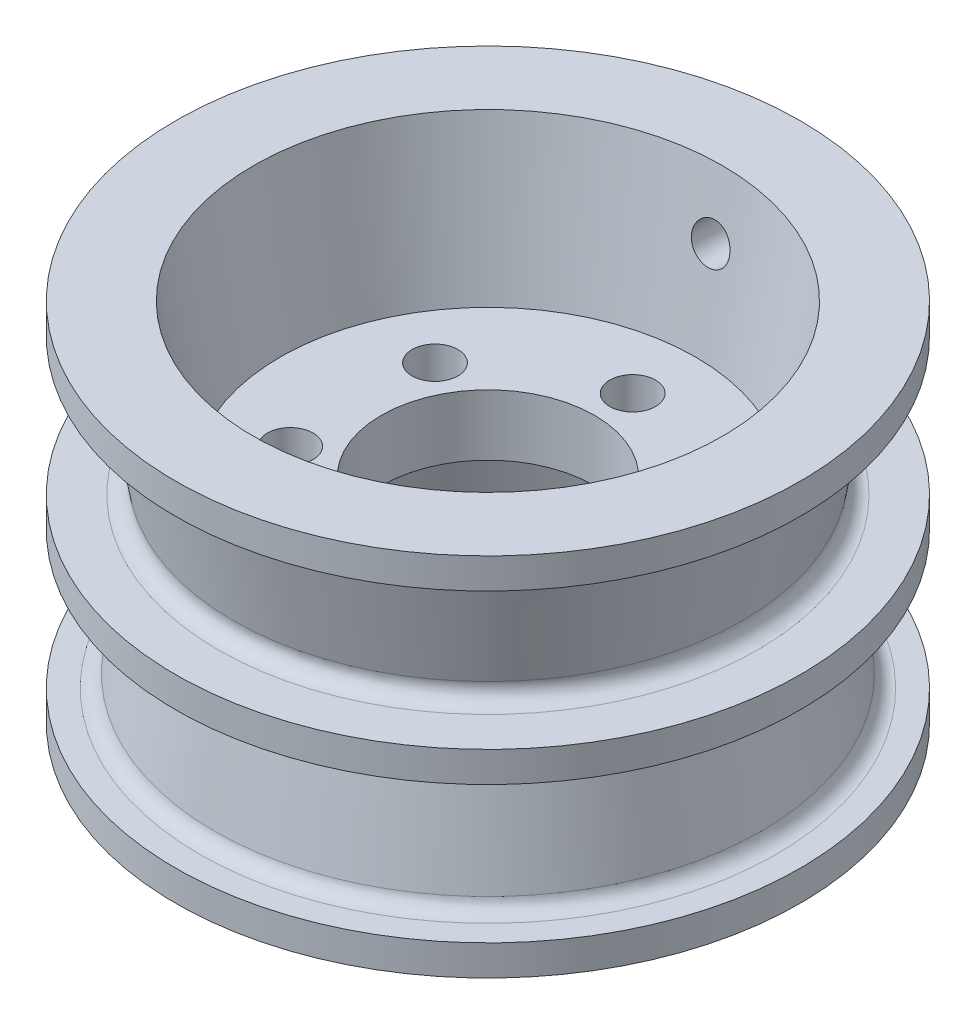
SolidWorks part; units mm, degrees
material "PA Type 6 尼龙"
ref_plane "前视基准面" through (0, 0, 0) normal (0, 0, 1) x (1, 0, 0)
ref_plane "上视基准面" through (0, 0, 0) normal (0, 1, 0) x (1, 0, 0)
ref_plane "右视基准面" through (0, 0, 0) normal (1, 0, 0) x (0, 0, -1)
sketch "草图2" plane through (0, 0, 0) normal (1, 0, 0) x (0, 0, -1)
  line L0 (20.5, 12) -> (20.5, 10)
  line L1 (20.5, 10) -> (18.0869, 10)
  line L2 (18.0869, 10) -> (16.5, 1)
  line L3 (16.5, 1) -> (20.5, 1)
  line L4 (20.5, 1) -> (20.5, -1)
  line L5 (20.5, -1) -> (16.5, -1)
  line L6 (16.5, -1) -> (18.0869, -10)
  line L7 (18.0869, -10) -> (20.5, -10)
  line L8 (20.5, -10) -> (20.5, -12)
  line L9 (20.5, -12) -> (15.3933, -12)
  line L10 (15.3933, -12) -> (13.63, -2)
  line L11 (13.63, -2) -> (0, -2)
  line L12 (0, -2) -> (0, 2)
  line L13 (0, 2) -> (13.63, 2)
  line L14 (13.63, 2) -> (15.3933, 12)
  line L15 (15.3933, 12) -> (20.5, 12)
  line L16 (0, 0) -> (20.5, 0) construction
  dimension "D1" = 4
  dimension "D2" = 2
  dimension "D3" = 24
  dimension "D4" = 10
  dimension "D5" = 16.5
  dimension "D6" = 3
  dimension "D7" = 20.5
revolve "旋转1" add sketch "草图2" angle 360 about L12
fillet "圆角1" radius 1 4 edges at (0, -10, -18.0869) (0, -1, -16.5) (0, 1, -16.5) (0, 10, -18.0869)
sketch "草图3" plane through (0, 2, 0) normal (0, 1, 0) x (1, 0, 0)
  circle A0 centre (0, 0) radius 7
  dimension "D1" = 14
extrude "切除-拉伸1" cut sketch "草图3" against normal blind 10
sketch "草图5" plane through (0, 0, 0) normal (0, 0, 1) x (1, 0, 0)
  line L0 (0, 7.9236) -> (0, 0) construction
  line L1 (-17.9412, 9.1736) -> (17.9412, 9.1736) construction
  circle A0 centre (0, 7.9236) radius 1.25
  dimension "D1" = 2.5
extrude "切除-拉伸2" cut sketch "草图5" against normal blind 24
mirror "镜向1" about plane through (0, 0, 0) normal (0, 1, 0) of "切除-拉伸2"
sketch "草图6" plane through (0, -2, 0) normal (0, -1, 0) x (1, 0, 0)
  circle A0 centre (0, 0) radius 9.5 construction
  circle A1 centre (0, 9.5) radius 1.505
  dimension "D1" = 19
  dimension "D2" = 3.01
extrude "切除-拉伸3" cut sketch "草图6" against normal blind 10
pattern_circular "阵列(圆周)1" count 6 over 360 about axis through (0, 0, 0) along (0, 1, 0) of "切除-拉伸3"
